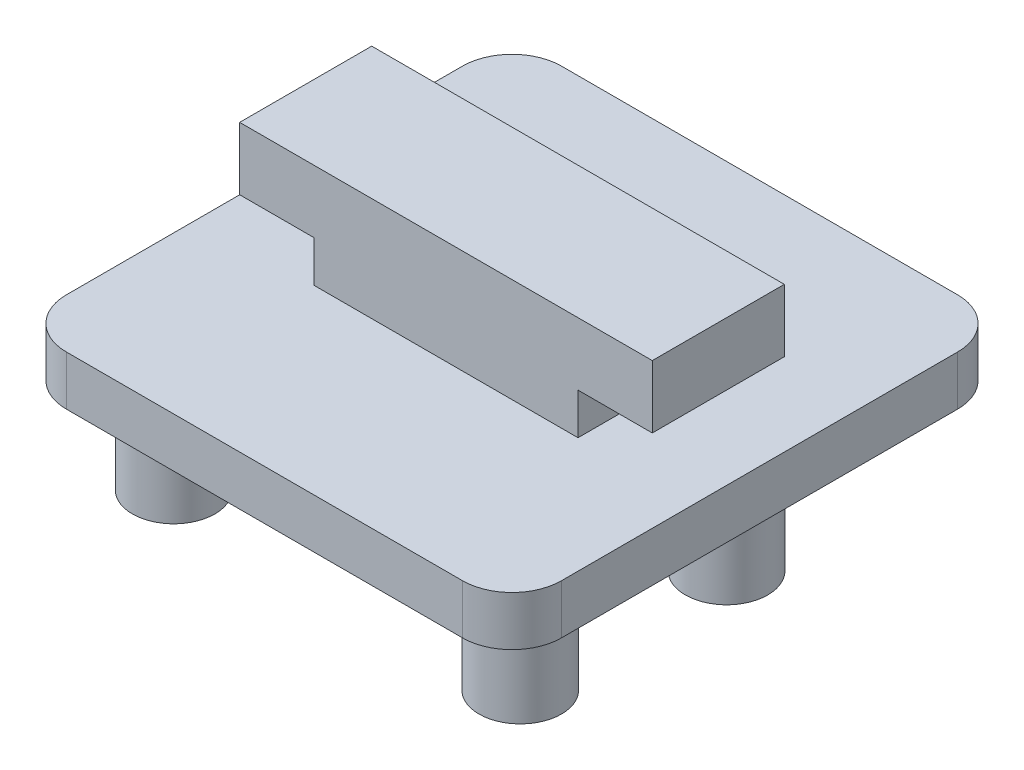
SolidWorks part; units mm, degrees
ref_plane "Спереди" through (0, 0, 0) normal (0, 0, 1) x (1, 0, 0)
ref_plane "Сверху" through (0, 0, 0) normal (0, 1, 0) x (1, 0, 0)
ref_plane "Справа" through (0, 0, 0) normal (1, 0, 0) x (0, 0, -1)
sketch "Эскиз1" plane through (0, 0, 0) normal (0, 1, 0) x (1, 0, 0)
  line L0 (-24.0785, -0.1685) -> (-24.0785, 2.8315) construction
  line L5 (-24.0785, 29.8315) -> (5.9215, -0.1685) construction
  line L6 (-24.0785, -0.1685) -> (5.9215, 29.8315) construction
  line L7 (-24.0785, 2.8315) -> (5.9215, 2.8315) construction
  line L8 (-24.0785, -0.1685) -> (-21.0785, -0.1685) construction
  line L9 (-21.0785, -0.1685) -> (-21.0785, 29.8315) construction
  line L10 (-24.0785, 29.8315) -> (-24.0785, 26.8315) construction
  line L11 (-24.0785, 26.8315) -> (5.9215, 26.8315) construction
  line L12 (5.9215, 29.8315) -> (2.9215, 29.8315) construction
  line L13 (2.9215, 29.8315) -> (2.9215, -0.1685) construction
  line L14 (-21.0785, 29.8315) -> (2.9215, 29.8315)
  line L15 (-24.0785, 26.8315) -> (-24.0785, 2.8315)
  line L16 (-21.0785, -0.1685) -> (2.9215, -0.1685)
  line L17 (5.9215, 2.8315) -> (5.9215, 26.8315)
  arc A0 (2.9215, -0.1685) -> (5.9215, 2.8315) centre (2.9215, 2.8315) ccw
  arc A1 (-24.0785, 2.8315) -> (-21.0785, -0.1685) centre (-21.0785, 2.8315) ccw
  arc A2 (-24.0785, 26.8315) -> (-21.0785, 29.8315) centre (-21.0785, 26.8315) cw
  arc A3 (5.9215, 26.8315) -> (2.9215, 29.8315) centre (2.9215, 26.8315) ccw
  point P0 (-9.0785, 14.8315)
extrude "Бобышка-Вытянуть2" add sketch "Эскиз1" along normal blind 3
sketch "Эскиз4" plane through (0, 0, 0) normal (0, -1, 0) x (1, 0, 0)
  line L0 (-9.0785, -29.8315) -> (-9.0785, 0.1685) construction
  line L1 (2.9215, -29.8315) -> (-21.0785, -29.8315) construction
  line L2 (-21.0785, 0.1685) -> (2.9215, 0.1685) construction
  line L3 (-24.0785, -14.8315) -> (5.9215, -14.8315) construction
  line L4 (-24.0785, -26.8315) -> (-24.0785, -2.8315) construction
  line L5 (5.9215, -2.8315) -> (5.9215, -26.8315) construction
  line L6 (3.4215, -2.8315) -> (1.4215, -2.8315) construction
  line L7 (1.4215, -2.8315) -> (1.4215, -4.8315) construction
  line L8 (3.4215, -26.8315) -> (-21.5785, -26.8315) construction
  line L9 (-21.5785, -26.8315) -> (-21.5785, -2.8315) construction
  line L10 (-21.5785, -2.8315) -> (3.4215, -2.8315) construction
  line L11 (3.4215, -2.8315) -> (3.4215, -26.8315) construction
  line L12 (-21.5785, -2.8315) -> (-19.5785, -2.8315)
  line L13 (-19.5785, -2.8315) -> (-19.5785, -4.8315)
  line L15 (1.4215, -26.8315) -> (1.4215, -17.3315) construction
  line L16 (1.4215, -17.3315) -> (-19.5785, -17.3315) construction
  circle A0 centre (1.4215, -4.8315) radius 2.5
  circle A1 centre (1.4215, -4.8315) radius 0.95
  circle A2 centre (-19.5785, -4.8315) radius 2.5
  circle A3 centre (-19.5785, -4.8315) radius 0.9731
  circle A4 centre (1.4215, -17.3315) radius 2.5
  circle A5 centre (1.4215, -17.3315) radius 0.95
  circle A6 centre (-19.5785, -17.3315) radius 2.5
  circle A7 centre (-19.5785, -17.3315) radius 0.95
  point P15 (-9.0785, -14.8315)
  point P18 (-9.0785, -14.8315)
extrude "Бобышка-Вытянуть5" add sketch "Эскиз4" along normal blind 6
ref_plane "Плоскость1" through (0, 3, 0) normal (0, 1, 0) x (1, 0, 0)
sketch "Эскиз6" plane through (0, 3, 0) normal (0, 1, 0) x (1, 0, 0)
  line L0 (-9.0785, 29.8315) -> (-9.0785, 18.8315) construction
  line L1 (2.9215, 29.8315) -> (-21.0785, 29.8315) construction
  line L2 (-9.0785, 18.8315) -> (-9.0785, 10.8315) construction
  line L3 (-9.0785, 10.8315) -> (-9.0785, -0.1685) construction
  line L4 (-21.0785, -0.1685) -> (2.9215, -0.1685) construction
  line L5 (-17.0785, 18.8315) -> (-1.0785, 18.8315)
  line L6 (-1.0785, 18.8315) -> (-1.0785, 10.8315)
  line L7 (-1.0785, 10.8315) -> (-17.0785, 10.8315)
  line L8 (-17.0785, 10.8315) -> (-17.0785, 18.8315)
  point P11 (-9.0785, 18.8315)
extrude "Бобышка-Вытянуть6" add sketch "Эскиз6" along normal blind 2.5
sketch "Эскиз7" plane through (0, 5.5, 0) normal (0, 1, 0) x (1, 0, 0)
  line L0 (-9.0785, 18.8315) -> (-21.5785, 18.8315)
  line L1 (-1.0785, 18.8315) -> (-17.0785, 18.8315) construction
  line L2 (-21.5785, 18.8315) -> (-21.5785, 10.8315)
  line L3 (-21.5785, 10.8315) -> (3.4215, 10.8315)
  line L4 (3.4215, 10.8315) -> (3.4215, 18.8315)
  line L5 (3.4215, 18.8315) -> (-9.0785, 18.8315)
extrude "Бобышка-Вытянуть7" add sketch "Эскиз7" along normal blind 3.8 contours L5 L0 L2 L3 L4
